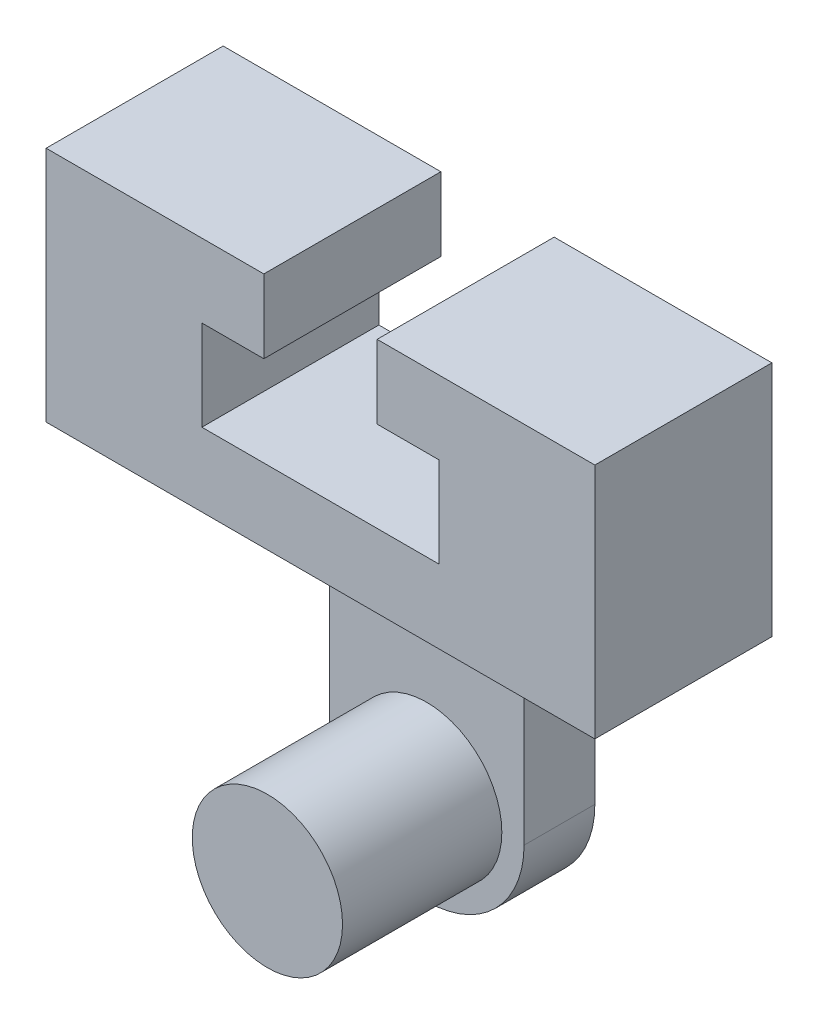
SolidWorks part; units mm, degrees
material "6061-T6 (SS)"
ref_plane "Front Plane" through (0, 0, 0) normal (0, 0, 1) x (1, 0, 0)
ref_plane "Top Plane" through (0, 0, 0) normal (0, 1, 0) x (1, 0, 0)
ref_plane "Right Plane" through (0, 0, 0) normal (1, 0, 0) x (0, 0, -1)
sketch "Sketch4" plane through (0, 0, 0) normal (0, 0, 1) x (1, 0, 0)
  line L0 (39.37, 0) -> (39.37, 34.036)
  line L1 (0, 0) -> (25.4, 0)
  line L2 (0, 0) -> (0, 34.036)
  line L3 (0, 34.036) -> (78.74, 34.036)
  line L4 (78.74, 0) -> (78.74, 34.036)
  line L5 (25.4, -33.528) -> (25.4, 0)
  line L6 (22.352, 10.541) -> (56.388, 10.541)
  line L7 (22.352, 10.541) -> (22.352, 23.495)
  line L8 (22.352, 23.495) -> (56.388, 23.495)
  line L9 (56.388, 10.541) -> (56.388, 23.495)
  line L10 (22.352, 10.541) -> (56.388, 23.495) construction
  line L11 (22.352, 23.495) -> (56.388, 10.541) construction
  line L12 (53.34, -33.528) -> (53.34, 0)
  line L13 (53.34, 0) -> (78.74, 0)
  arc A0 (25.4, -33.528) -> (53.34, -33.528) centre (39.37, -33.528) ccw
  point P7 (39.37, 17.018)
  point P13 (0, 0)
  dimension "D5" = 27.94
  dimension "D1" = 34.036
  dimension "D2" = 78.74
  dimension "D3" = 34.036
  dimension "D4" = 12.954
  dimension "D6" = 33.528
  dimension "D7" = 39.37
extrude "Boss-Extrude3" add sketch "Sketch4" along normal blind 25.4 separate body contours L5 L1 L2 L3 L4 L13 L12 A0
sketch "Sketch5" plane through (0, 0, 25.4) normal (0, 0, 1) x (1, 0, 0)
  line L0 (39.37, 34.036) -> (39.37, 0) construction
  line L1 (0, 34.036) -> (78.74, 34.036) construction
  line L2 (47.498, 23.495) -> (56.388, 23.495)
  line L3 (22.352, 10.541) -> (56.388, 10.541)
  line L4 (22.352, 10.541) -> (22.352, 23.495)
  line L5 (22.352, 23.495) -> (31.242, 23.495)
  line L6 (56.388, 10.541) -> (56.388, 23.495)
  line L7 (22.352, 10.541) -> (56.388, 23.495) construction
  line L8 (22.352, 23.495) -> (56.388, 10.541) construction
  line L10 (31.242, 23.495) -> (31.242, 34.036)
  line L11 (31.242, 34.036) -> (47.498, 34.036)
  line L12 (47.498, 23.495) -> (47.498, 34.036)
  point P5 (39.37, 17.018)
  dimension "D1" = 34.036
  dimension "D2" = 12.954
  dimension "D3" = 8.89
  dimension "D4" = 8.89
extrude "Cut-Extrude2" cut sketch "Sketch5" against normal through all
sketch "Sketch7" plane through (0, 0, 25.4) normal (0, 0, 1) x (1, 0, 0)
  line L1 (25.4, 0) -> (53.34, 0)
  line L2 (25.4, 0) -> (25.4, -33.528)
  line L4 (53.34, 0) -> (53.34, -33.528)
  arc A0 (25.4, -33.528) -> (53.34, -33.528) centre (39.37, -33.528) ccw
extrude "Cut-Extrude3" cut sketch "Sketch7" against normal blind 15.24
sketch "Sketch8" plane through (0, 0, 10.16) normal (0, 0, 1) x (1, 0, 0)
  circle A0 centre (39.37, -33.528) radius 10.7823
  dimension "D1" = 21.5646
extrude "Boss-Extrude4" add sketch "Sketch8" along normal blind 22.86
equation "\"F\"= 600"
equation "\"SF\"= 4"
equation "\"YM\"= 10000000"
equation "\"MaxDef\"= 0.005in"
equation "\"Length of Pin\"= 2"
equation "\"YS\"= 40000"
equation "\"Wofphi\"= 1.25"
equation "\"Le\"= 1.5"
equation "\"We\"= 3.1"
equation "\"Hb\"= 0.51"
equation "\"D_A\"= 0.849in"
equation "\"T_B\"= 0.137in"
equation "\"W_C\"= 1.342in"
equation "\"T_D\"= 0.0436in"
equation "\"Wa\"= 1"
equation "\"T_E\"= 1.342in"
equation "\"AllowStress\"= \"YS\" / \"SF\""
